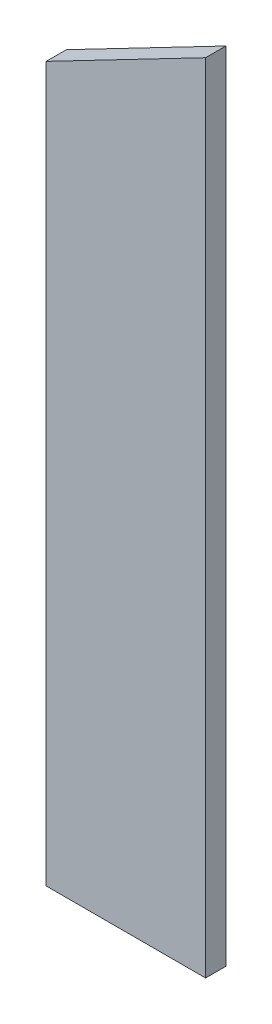
SolidWorks part; units mm, degrees
ref_plane "Front Plane" through (0, 0, 0) normal (0, 0, 1) x (1, 0, 0)
ref_plane "Top Plane" through (0, 0, 0) normal (0, 1, 0) x (1, 0, 0)
ref_plane "Right Plane" through (0, 0, 0) normal (1, 0, 0) x (0, 0, -1)
sketch "Sketch1" plane through (0, 0, 0) normal (0, 0, 1) x (1, 0, 0)
  line L0 (-25, -112) -> (-25, 112)
  line L1 (-25, 112) -> (25, 138)
  line L2 (25, 138) -> (25, -112)
  line L3 (25, -112) -> (-25, -112)
  line L4 (-25, 0) -> (25, 0) construction
  line L5 (25, 110.25) -> (25, 74.5)
  line L7 (25, 138) -> (25, 110.25)
  line L13 (25, 74.5) -> (25, 42.75)
  line L17 (25, 42.75) -> (25, 11)
  line L21 (25, 11) -> (25, -20.75)
  line L25 (25, -20.75) -> (25, -52.5)
  line L29 (25, -52.5) -> (25, -84.25)
  line L33 (25, -84.25) -> (25, -112)
  line L46 (12.3, -112) -> (25, -112)
  point P2 (0, 0)
  dimension "D1" = 50
  dimension "D2" = 250
  dimension "D3" = 224
  dimension "D5" = 8
extrude "Boss-Extrude1" add sketch "Sketch1" along normal blind 6.35
equation "\"Height\"= 12in"
equation "\"Depth\"= 7in"
equation "\"WallThickness\"= 0.25in"
equation "\"FloorThickness\"= 0.25in"
equation "\"D1@Boss-Extrude1\"=\"WallThickness\""
equation "\"Width\" = 30in"
